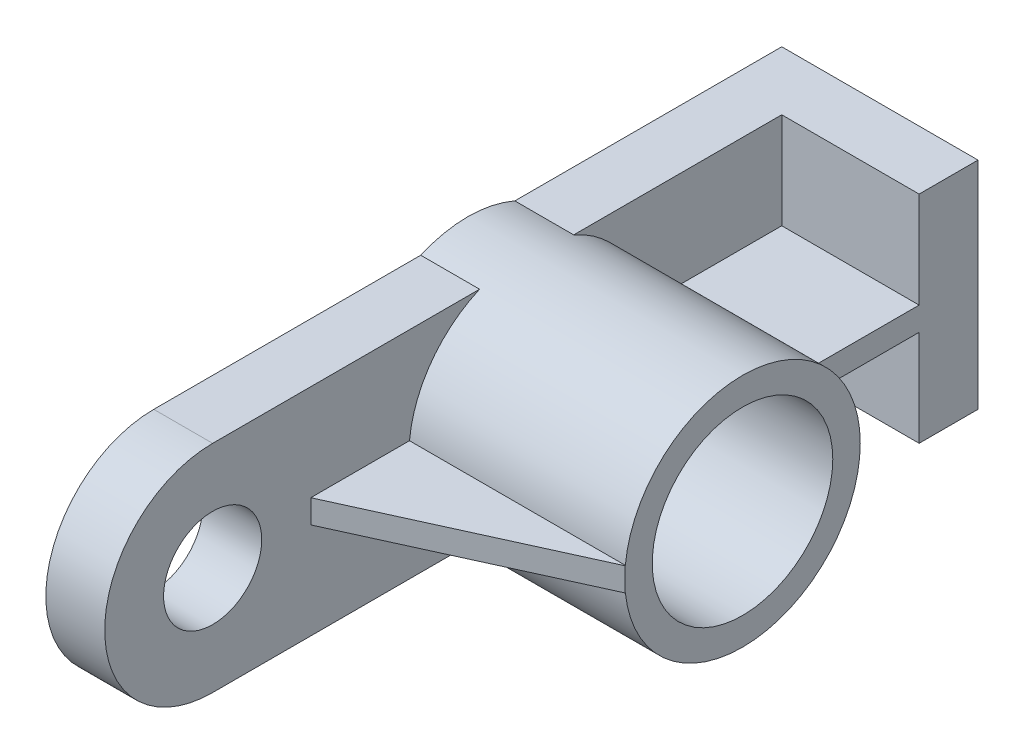
SolidWorks part; units mm, degrees
ref_plane "Front Plane" through (0, 0, 0) normal (0, 0, 1) x (1, 0, 0)
ref_plane "Top Plane" through (0, 0, 0) normal (0, 1, 0) x (1, 0, 0)
ref_plane "Right Plane" through (0, 0, 0) normal (1, 0, 0) x (0, 0, -1)
sketch "Sketch1" plane through (0, 0, 0) normal (1, 0, 0) x (0, 0, -1)
  line L1 (-80, 27.5) -> (80, 27.5)
  line L3 (-80, -27.5) -> (80, -27.5)
  line L4 (80, 27.5) -> (80, -27.5)
  line L5 (-80, 27.5) -> (80, -27.5) construction
  line L6 (-80, -27.5) -> (80, 27.5) construction
  arc A0 (-80, -27.5) -> (-80, 27.5) centre (-80, 0) cw
  point P0 (0, 0)
  dimension "D1" = 27.5
  dimension "D2" = 160
extrude "Boss-Extrude1" add sketch "Sketch1" along normal blind 15
sketch "Sketch2" plane through (15, 0, 0) normal (1, 0, 0) x (0, 0, -1)
  circle A0 centre (0, 0) radius 30
  dimension "D1" = 60
extrude "Boss-Extrude2" add sketch "Sketch2" along normal blind 55 and the other way blind 15
hole_wizard "Hole1" positions "Sketch3" profile "Sketch4" legacy end condition up to next
sketch "Sketch3" plane through (70, 0, 0) normal (1, 0, 0) x (0, 0, -1)
  point P0 (0, 0)
sketch "Sketch4" plane through (70, 0, 0) normal (0, 1, 0) x (0, 0, -1)
  line L0 (0, 0) -> (0, 70)
  line L1 (0, 70) -> (23, 70)
  line L2 (23, 70) -> (23, 0)
  line L3 (23, 0) -> (0, 0)
  line L4 (0, 110) -> (0, -10) construction
  dimension "Diameter" = 46
  dimension "Depth" = 70
sketch "Sketch5" plane through (0, 0, -80) normal (0, 0, -1) x (-1, 0, 0)
  line L1 (0, 27.5) -> (-50, 27.5)
  line L2 (0, 27.5) -> (0, -27.5)
  line L3 (0, -27.5) -> (-50, -27.5)
  line L4 (-50, 27.5) -> (-50, -27.5)
  dimension "D1" = 55
  dimension "D2" = 50
extrude "Boss-Extrude3" add sketch "Sketch5" against normal blind 15
sketch "Sketch6" plane through (0, 0, 0) normal (0, 1, 0) x (1, 0, 0)
  line L0 (50, 65) -> (50, 30)
  line L1 (70, 30) -> (15, 30) construction
rib "Rib1" sketch "Sketch6" sketch "Sketch6" thickness 6 extrusion direction parallel to sketch draft on no parameters "D1"=6
sketch "Sketch7" plane through (0, 0, 0) normal (0, 1, 0) x (1, 0, 0)
  line L0 (70, -30) -> (15, -55)
  line L1 (15, -11.9896) -> (15, -80) construction
  line L2 (15, -55) -> (15, -28)
  line L5 (70, -30) -> (70, 30) construction
  line L6 (70, -28) -> (15, -28)
  line L8 (70, -28) -> (70, -30)
  point P5 (15, -25.6706)
  dimension "D1" = 25
  dimension "D2" = 2
extrude "Boss-Extrude5" add sketch "Sketch7" along normal mid plane 6
hole_wizard "Hole2" positions "Sketch8" profile "Sketch9" legacy end condition up to next
sketch "Sketch8" plane through (15, 0, 0) normal (1, 0, 0) x (0, 0, -1)
  point P0 (-80, 0)
sketch "Sketch9" plane through (15, 0, 80) normal (0, 1, 0) x (0, 0, -1)
  line L0 (0, 0) -> (0, 15)
  line L1 (0, 15) -> (12.5, 15)
  line L2 (12.5, 15) -> (12.5, 0)
  line L3 (12.5, 0) -> (0, 0)
  line L4 (0, 110) -> (0, -10) construction
  dimension "Diameter" = 25
  dimension "Depth" = 15
